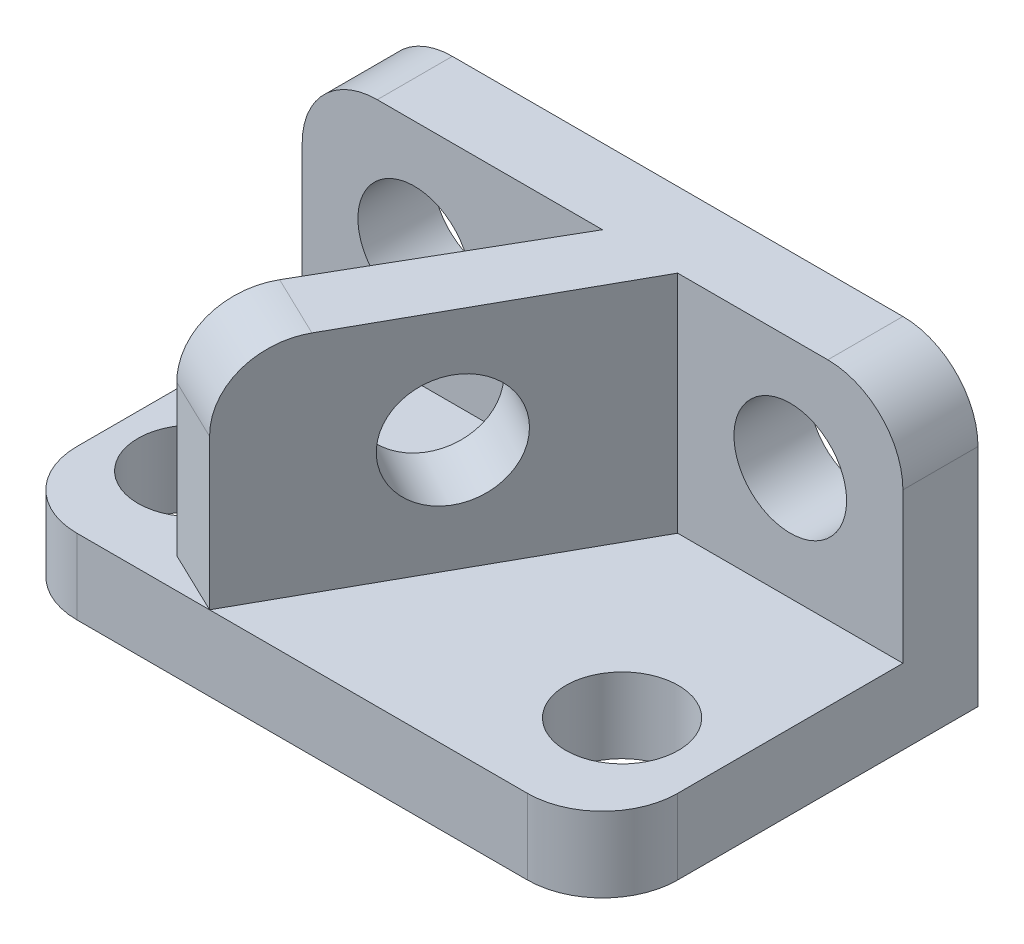
SolidWorks part; units mm, degrees
ref_plane "Front Plane" through (0, 0, 0) normal (0, 0, 1) x (1, 0, 0)
ref_plane "Top Plane" through (0, 0, 0) normal (0, 1, 0) x (1, 0, 0)
ref_plane "Right Plane" through (0, 0, 0) normal (1, 0, 0) x (0, 0, -1)
sketch "Sketch1" plane through (0, 0, 0) normal (0, 1, 0) x (1, 0, 0)
  line L1 (-85.9783, 24.2391) -> (-5.9783, 24.2391)
  line L2 (-85.9783, 24.2391) -> (-85.9783, 14.2391)
  line L3 (-85.9783, 14.2391) -> (-5.9783, 14.2391)
  line L4 (-5.9783, 24.2391) -> (-5.9783, 14.2391)
  line L5 (-85.9783, 24.2391) -> (-5.9783, 14.2391) construction
  line L6 (-85.9783, 14.2391) -> (-5.9783, 24.2391) construction
  point P0 (-45.9783, 19.2391)
  dimension "D1" = 10
  dimension "D2" = 80
extrude "Boss-Extrude1" add sketch "Sketch1" against normal blind 40
sketch "Sketch3" plane through (0, 0, -14.2391) normal (0, 0, 1) x (1, 0, 0)
  line L0 (-85.9783, -40) -> (-85.9783, 0) construction
  line L1 (-85.9783, -30) -> (-5.9783, -30)
  line L2 (-85.9783, -30) -> (-85.9783, -40)
  line L3 (-85.9783, -40) -> (-5.9783, -40)
  line L4 (-5.9783, -30) -> (-5.9783, -40)
  line L5 (-85.9783, -30) -> (-5.9783, -40) construction
  line L6 (-85.9783, -40) -> (-5.9783, -30) construction
  point P0 (-45.9783, -35)
  point P6 (-75.9783, -30.9412)
  dimension "D1" = 10
  dimension "D2" = 80
extrude "Boss-Extrude2" add sketch "Sketch3" along normal blind 40
sketch "Sketch7" plane through (0, -30, 0) normal (0, 1, 0) x (1, 0, 0)
  line L0 (-45.9783, 14.2391) -> (-66.7318, -21.7071)
  line L1 (-5.9783, 14.2391) -> (-85.9783, 14.2391) construction
  line L2 (-66.7318, -21.7071) -> (-58.3129, -25.7609)
  line L4 (-58.3129, -25.7609) -> (-35.9783, 14.2391)
  line L6 (-5.9783, 14.2391) -> (-35.9783, 14.2391)
  line L10 (-5.9783, 14.2391) -> (-85.9783, 14.2391)
  line L11 (-85.9783, 14.2391) -> (-85.9783, -25.7609)
  line L12 (-85.9783, -25.7609) -> (-5.9783, -25.7609)
  line L13 (-5.9783, -25.7609) -> (-5.9783, 14.2391)
  line L14 (-45.9783, 14.2391) -> (-85.9783, 14.2391)
  line L15 (-85.9783, 14.2391) -> (-85.9783, -25.7609)
  line L16 (-85.9783, -25.7609) -> (-5.9783, -25.7609)
  line L17 (-5.9783, -25.7609) -> (-5.9783, 14.2391)
  point P4 (-45.9783, -25.7609)
  point P6 (-53.5376, -25.7609)
  point P7 (-69.0422, -25.7087)
  point P9 (-67.8425, -23.6309)
  point P10 (0, 0)
  point P11 (-58.3129, -25.7609)
  point P14 (0, 0)
  point P16 (-69.0723, -25.7609)
  point P18 (-66.7318, -21.7071)
  line M7 (-5.9783, 14.2391) -> (-85.9783, 14.2391)
  dimension "D1" = 60
  dimension "D4" = 10
  dimension "D5" = 0
extrude "Boss-Extrude6" add sketch "Sketch7" along normal blind 30 contours L2 L4 L0 M7
sketch "Sketch8" plane through (0, -30, 0) normal (0, 1, 0) x (1, 0, 0)
  line L0 (-5.9783, -25.7609) -> (-58.3129, -25.7609) construction
  line L1 (-58.3129, -25.7609) -> (-85.9783, -25.7609) construction
  circle A0 centre (-18.3764, -10.7609) radius 7.5
  circle A1 centre (-75.3589, -10.7609) radius 7.5
  point P8 (-18.3764, -10.7609)
  point P9 (-75.3589, -10.7609)
  point P10 (-23.6021, -9.9754)
  dimension "D1" = 15
  dimension "D3" = 15
  dimension "D2" = 15
  dimension "D4" = 7.5
extrude "Cut-Extrude1" cut sketch "Sketch8" against normal up to vertex (10 mm away)
sketch "Sketch9" plane through (0, 0, -14.2391) normal (0, 0, 1) x (1, 0, 0)
  line L0 (-35.9783, 0) -> (-35.9783, -30) construction
  line L1 (-45.9783, -30) -> (-85.9783, -30) construction
  line L2 (-5.9783, -30) -> (-35.9783, -30) construction
  circle A0 centre (-20.9783, -15) radius 7.5
  circle A1 centre (-71.0572, -15) radius 7.5
  dimension "D1" = 15
  dimension "D2" = 15
  dimension "D3" = 15
  dimension "D4" = 15
  dimension "D5" = 15
extrude "Cut-Extrude2" cut sketch "Sketch9" against normal blind 30
fillet "Fillet1" radius 10 5 edges at (-5.9783, 0, -19.2391) (-5.9783, -35, 25.7609) (-85.9783, -35, 25.7609) (-62.5223, 0, 23.734) (-85.9783, 0, -19.2391)
sketch "Sketch10" plane through (-33.4882, 0, -18.6986) normal (0.8731, 0, 0.4875) x (0.4875, 0, -0.8731)
  line L0 (-50.9206, -30) -> (-5.1076, -30) construction
  line L1 (-50.9206, -10) -> (-50.9206, -30) construction
  line L2 (-5.1076, 0) -> (-5.1076, -30) construction
  circle A0 centre (-27.1076, -15) radius 7.5
  point P6 (0, 0)
  point P8 (-5.1076, -15.575)
  dimension "D1" = 15
  dimension "D2" = 15
  dimension "D3" = 45.813
  dimension "D4" = 22
extrude "Cut-Extrude3" cut sketch "Sketch10" against normal blind 12
